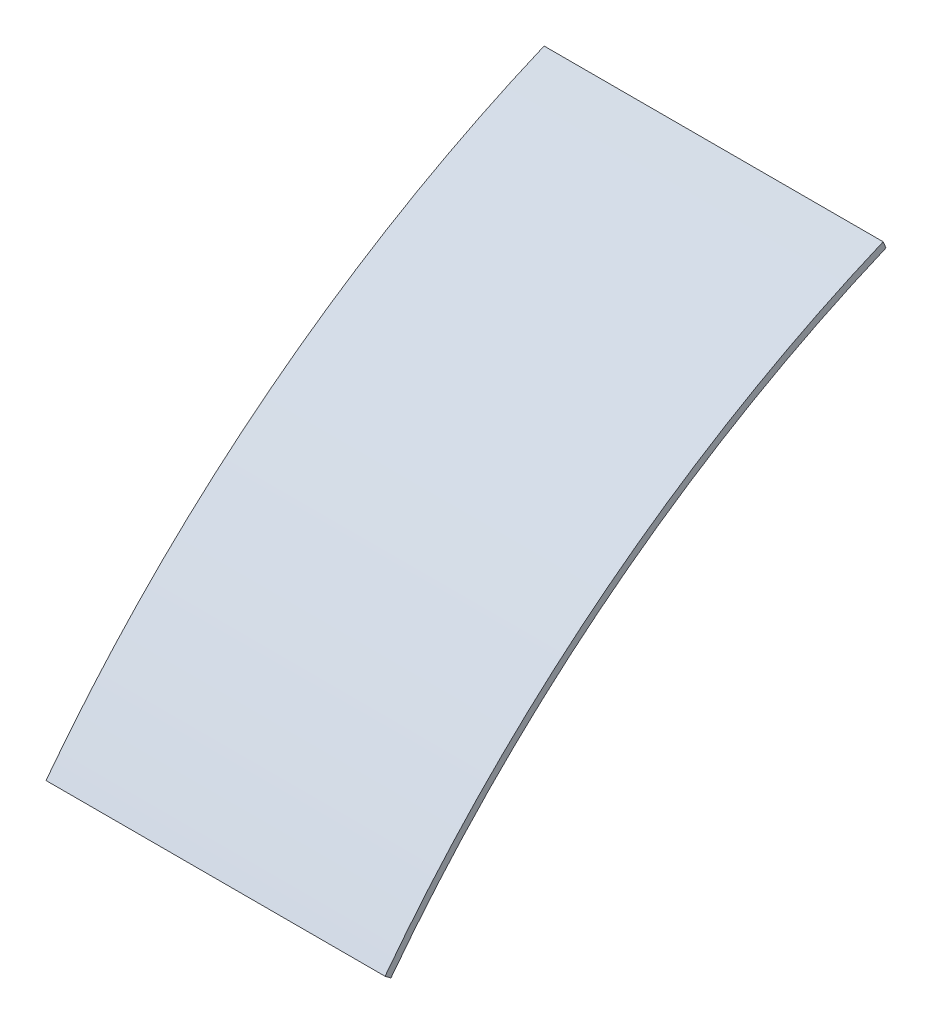
SolidWorks part; units mm, degrees
material "Acrylic (Medium-high impact)"
ref_plane "Front Plane" through (0, 0, 0) normal (0, 0, 1) x (1, 0, 0)
ref_plane "Top Plane" through (0, 0, 0) normal (0, 1, 0) x (1, 0, 0)
ref_plane "Right Plane" through (0, 0, 0) normal (1, 0, 0) x (0, 0, -1)
sketch "Sketch1" plane through (0, 0, 0) normal (1, 0, 0) x (0, 0, -1)
  line L0 (-212.2627, -168.8246) -> (-214.7933, -166.9072)
  line L5 (0, 0) -> (1.2332, -2.9257)
  arc A0 (0, 0) -> (-214.7933, -166.9072) centre (204.0566, -484.2636) ccw
  arc A1 (1.2332, -2.9257) -> (-212.2627, -168.8246) centre (204.0566, -484.2636) ccw
  arc A2 (0.6166, -1.4629) -> (-213.528, -167.8659) centre (204.0566, -484.2636) ccw
  dimension "D3" = 523.9126
  dimension "D1" = 3.175
  dimension "D2" = 274.32
extrude "Boss-Extrude1" add sketch "Sketch1" along normal blind 146.2024 contours L5 A2 L0 A1 | A2 L5 A0 L0
sketch "Sketch2" plane through (0, 0, 0) normal (-1, 0, 0) x (0, 0, 1)
  line L2 (-1.4789, -3.5086) -> (0.2457, 0.5829)
  line L3 (6.0971, -1.8835) -> (4.3725, -5.9751)
  line L4 (-1.4789, -3.5086) -> (4.3725, -5.9751)
  line L5 (6.0971, -1.8835) -> (0.2457, 0.5829)
  line L6 (0, 0) -> (-1.2332, -2.9257) construction
  point P11 (-0.6166, -1.4629)
  point P12 (-0.6166, -1.4629)
  dimension "D1" = 6.35
extrude "Cut-Extrude1" [suppressed] cut sketch "Sketch2" against normal through all
equation "\"WallThickness\"=0.125"
equation "\"D1\"= \"WallThickness\""
equation "\"D1@Sketch1\"=\"WallThickness\""
